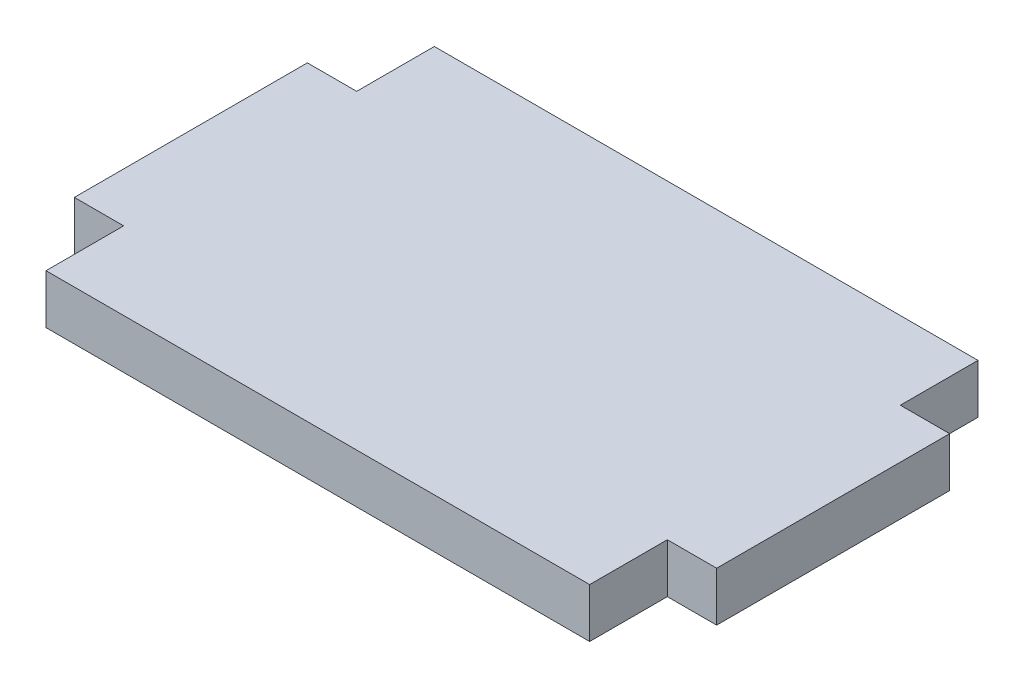
SolidWorks part; units mm, degrees
ref_plane "Front Plane" through (0, 0, 0) normal (0, 0, 1) x (1, 0, 0)
ref_plane "Top Plane" through (0, 0, 0) normal (0, 1, 0) x (1, 0, 0)
ref_plane "Right Plane" through (0, 0, 0) normal (1, 0, 0) x (0, 0, -1)
sketch "Sketch1" plane through (0, 0, 0) normal (0, 1, 0) x (1, 0, 0)
  line L0 (-49.076, 5.5051) -> (-42.726, 5.5051)
  line L1 (-42.726, 5.5051) -> (-42.726, 15.5051)
  line L2 (-42.726, 15.5051) -> (27.274, 15.5051)
  line L3 (27.274, 15.5051) -> (27.274, 5.5051)
  line L4 (27.274, 5.5051) -> (33.624, 5.5051)
  line L5 (33.624, 5.5051) -> (33.624, -24.4949)
  line L6 (33.624, -24.4949) -> (27.274, -24.4949)
  line L7 (27.274, -24.4949) -> (27.274, -34.4949)
  line L8 (27.274, -34.4949) -> (-42.726, -34.4949)
  line L9 (-42.726, -34.4949) -> (-42.726, -24.4949)
  line L10 (-42.726, -24.4949) -> (-49.076, -24.4949)
  line L11 (-49.076, -24.4949) -> (-49.076, 5.5051)
  dimension "D1" = 50
  dimension "D2" = 30
  dimension "D3" = 6.35
  dimension "D4" = 70
extrude "Body" add sketch "Sketch1" along normal blind 6.35
